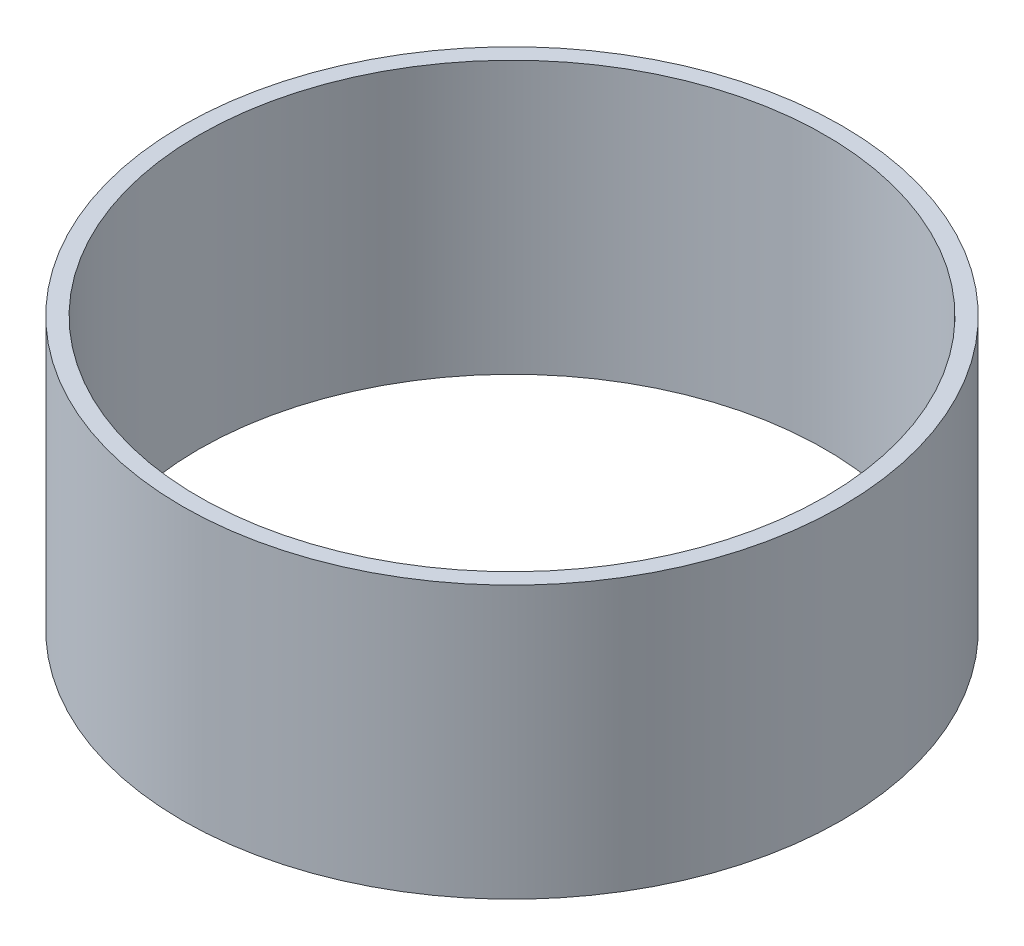
SolidWorks part; units mm, degrees
ref_plane "Front Plane" through (0, 0, 0) normal (0, 0, 1) x (1, 0, 0)
ref_plane "Top Plane" through (0, 0, 0) normal (0, 1, 0) x (1, 0, 0)
ref_plane "Right Plane" through (0, 0, 0) normal (1, 0, 0) x (0, 0, -1)
sketch "Sketch1" plane through (0, 0, 0) normal (0, 1, 0) x (1, 0, 0)
  circle A0 centre (0, 0) radius 60
  dimension "D1" = 120
extrude "Extrude-Thin1" add sketch "Sketch1" along normal blind 49.5 thin thin type one direction reverse wall 3
